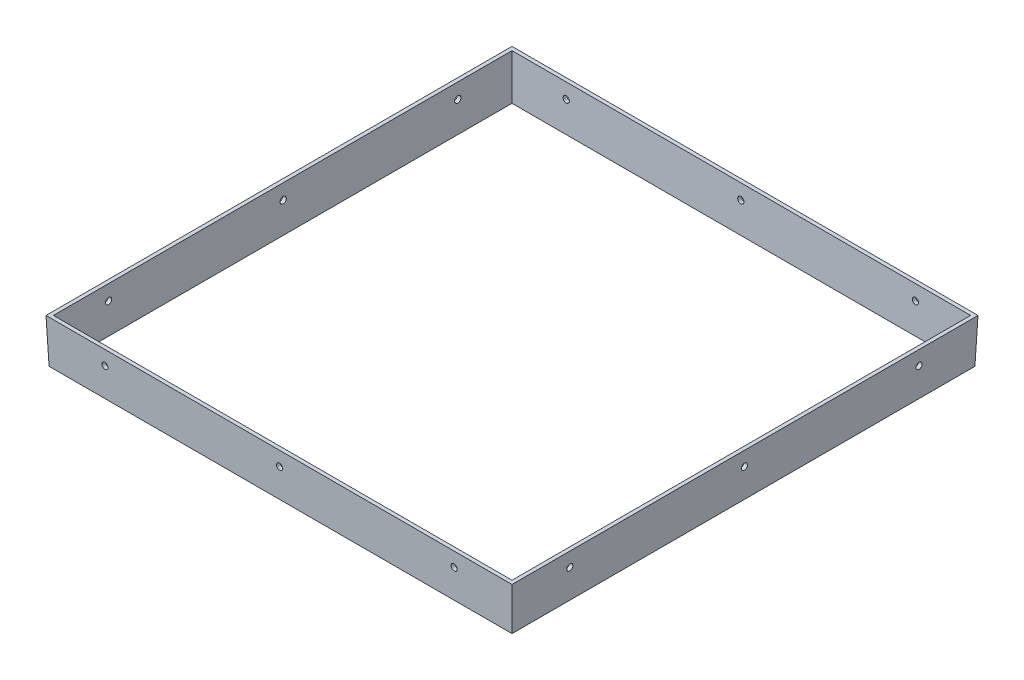
SolidWorks part; units mm, degrees
material "Alumina"
ref_plane "Front Plane" through (0, 0, 0) normal (0, 0, 1) x (1, 0, 0)
ref_plane "Top Plane" through (0, 0, 0) normal (0, 1, 0) x (1, 0, 0)
ref_plane "Right Plane" through (0, 0, 0) normal (1, 0, 0) x (0, 0, -1)
sketch "Sketch2" plane through (0, 0, 0) normal (0, 1, 0) x (1, 0, 0)
  line L0 (-125.93, -125.93) -> (125.93, -125.93)
  line L1 (-125.93, -125.93) -> (-125.93, 125.93)
  line L2 (-125.93, 125.93) -> (125.93, 125.93)
  line L3 (125.93, -125.93) -> (125.93, 125.93)
  line L4 (-125.93, -125.93) -> (125.93, 125.93) construction
  line L5 (-125.93, 125.93) -> (125.93, -125.93) construction
  point P0 (0, 0)
  dimension "D2" = 251.86
extrude "Boss-Extrude1" add sketch "Sketch2" along normal blind 24 draft 2 draft outward yes
shell "Shell1" thickness 2
sketch "Sketch3" plane through (-125.7766, -4.3922, 0) normal (-0.9994, -0.0349, 0) x (0, 0, 1)
  line L0 (-126.7681, 28.4095) -> (126.7681, 28.4095) construction
  circle A0 centre (-95, 20.4095) radius 1.7
  circle A1 centre (0, 20.4095) radius 1.7
  circle A2 centre (95, 20.4095) radius 1.7
  dimension "D1" = 3.4
  dimension "D2" = 8
  dimension "D3" = 95
  dimension "D4" = 95
extrude "Cut-Extrude1" cut sketch "Sketch3" against normal blind 10 and the other way through all
mirror "Mirror1" about plane through (0, 0, 0) normal (1, 0, 0) of "Cut-Extrude1"
sketch "Sketch4" plane through (0, -4.3922, -125.7766) normal (0, -0.0349, -0.9994) x (-1, 0, 0)
  line L0 (-126.7681, 28.4095) -> (126.7681, 28.4095) construction
  circle A0 centre (-95, 20.4095) radius 1.7
  circle A1 centre (0, 20.4095) radius 1.7
  circle A2 centre (95, 20.4095) radius 1.7
  dimension "D4" = 3.4
  dimension "D1" = 8
  dimension "D2" = 95
  dimension "D3" = 95
extrude "Cut-Extrude2" cut sketch "Sketch4" against normal blind 10
mirror "Mirror2" about plane through (0, 0, 0) normal (0, 0, 1) of "Cut-Extrude2"
